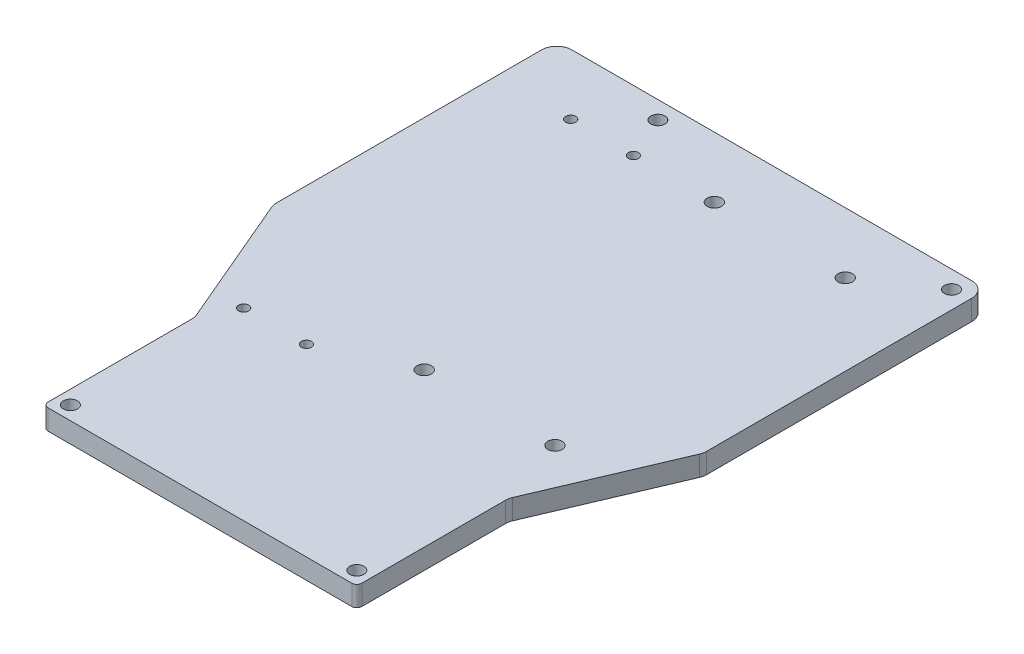
SolidWorks part; units mm, degrees
ref_plane "Front Plane" through (0, 0, 0) normal (0, 0, 1) x (1, 0, 0)
ref_plane "Top Plane" through (0, 0, 0) normal (0, 1, 0) x (1, 0, 0)
ref_plane "Right Plane" through (0, 0, 0) normal (1, 0, 0) x (0, 0, -1)
sketch "Sketch1" plane through (0, 0, 0) normal (0, 1, 0) x (1, 0, 0)
  line L0 (-42.2601, -28.5633) -> (-31.2399, -54.4367)
  line L1 (-42.5, -28) -> (42.5, -28) construction
  line L2 (-42.5, -27.3877) -> (-42.5, 25)
  line L3 (-39.5, 28) -> (39.5, 28)
  line L4 (42.5, -27.3877) -> (42.5, 25)
  line L5 (-42.5, -28) -> (42.5, 28) construction
  line L6 (-42.5, 28) -> (42.5, -28) construction
  line L7 (-30, -85) -> (30, -85)
  line L8 (-31, -85) -> (-31, -43) construction
  line L9 (-31, -43) -> (31, -43) construction
  line L10 (31, -85) -> (31, -43) construction
  line L11 (-31, -85) -> (31, -43) construction
  line L12 (-31, -43) -> (31, -85) construction
  line L13 (-31, -55.6123) -> (-31, -84)
  line L14 (42.2601, -28.5633) -> (31.2399, -54.4367)
  line L15 (31, -55.6123) -> (31, -84)
  arc A0 (39.5, 28) -> (42.5, 25) centre (39.5, 25) cw
  arc A1 (-42.5, 25) -> (-39.5, 28) centre (-39.5, 25) cw
  arc A2 (-30, -85) -> (-31, -84) centre (-30, -84) cw
  arc A3 (30, -85) -> (31, -84) centre (30, -84) ccw
  arc A4 (-31.2399, -54.4367) -> (-31, -55.6123) centre (-34, -55.6123) cw
  arc A5 (31.2399, -54.4367) -> (31, -55.6123) centre (34, -55.6123) ccw
  arc A6 (42.2601, -28.5633) -> (42.5, -27.3877) centre (39.5, -27.3877) ccw
  arc A7 (-42.2601, -28.5633) -> (-42.5, -27.3877) centre (-39.5, -27.3877) cw
  point P0 (0, 0)
  point P12 (0, -64)
  point P31 (-31, -55)
  point P34 (31, -55)
  dimension "D3" = 3
  dimension "D8" = 1
  dimension "D9" = 3
  dimension "D1" = 85
  dimension "D2" = 56
  dimension "D4" = 62
  dimension "D5" = 42
  dimension "D6" = 15
  dimension "D7" = 30
extrude "Boss-Extrude1" add sketch "Sketch1" along normal blind 4
sketch "Sketch2" plane through (0, 4, 0) normal (0, 1, 0) x (1, 0, 0)
  line L0 (39.5, 28) -> (-39.5, 28) construction
  line L1 (42.5, -27.3877) -> (42.5, 25) construction
  line L2 (-31, -55.6123) -> (-31, -84) construction
  line L3 (-30, -85) -> (30, -85) construction
  line L5 (31, -84) -> (31, -55.6123) construction
  line L6 (42.5, -27.3877) -> (42.5, 25) construction
  circle A0 centre (39, 24.5) radius 1.4
  circle A1 centre (-19, 24.5) radius 1.4
  circle A4 centre (-28.3, -82.3) radius 1.4
  circle A7 centre (28.3, -82.3) radius 1.4
  circle A8 centre (26.5, 16) radius 1.425
  circle A9 centre (0.65, 16) radius 1.425
  circle A10 centre (26.5, -41.35) radius 1.425
  circle A11 centre (0.65, -41.35) radius 1.425
  circle A12 centre (-15.35, 16) radius 1
  circle A13 centre (-27.75, 16) radius 1
  circle A14 centre (-15.35, -48.6) radius 1
  circle A15 centre (-27.75, -48.6) radius 1
  point P38 (0, 0)
  point P41 (0, 0)
  point P42 (0, 0)
  dimension "D3" = 2.8
  dimension "D4" = 2.8
  dimension "D5" = 57.35
  dimension "D6" = 16
  dimension "D9" = 2
  dimension "D14" = 2.8
  dimension "D15" = 2.8
  dimension "D12" = 2.7
  dimension "D18" = 12
  dimension "D19" = 2.85
  dimension "D1" = 3.5
  dimension "D2" = 3.5
  dimension "D7" = 16
  dimension "D8" = 58
  dimension "D10" = 2.7
  dimension "D11" = 2.7
  dimension "D13" = 12.4
  dimension "D20" = 25.85
  dimension "D21" = 64.6
extrude "Cut-Extrude1" cut sketch "Sketch2" against normal through all
